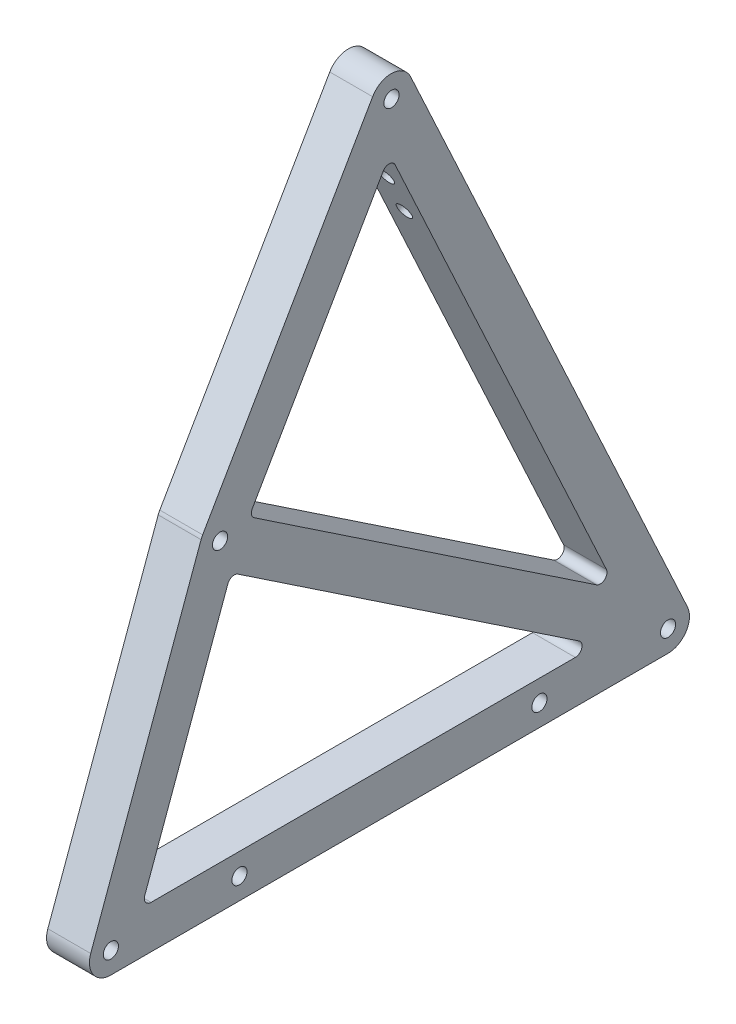
SolidWorks part; units mm, degrees
ref_plane "Front Plane" through (0, 0, 0) normal (0, 0, 1) x (1, 0, 0)
ref_plane "Top Plane" through (0, 0, 0) normal (0, 1, 0) x (1, 0, 0)
ref_plane "Right Plane" through (0, 0, 0) normal (1, 0, 0) x (0, 0, -1)
sketch "Sketch1" plane through (0, 0, 0) normal (1, 0, 0) x (0, 0, -1)
  line L0 (0, 0) -> (50.8, 87.9882) construction
  line L1 (0, 0) -> (-32.357, -88.9) construction
  line L2 (-32.357, -88.9) -> (132.743, -88.9) construction
  line L3 (132.743, -88.9) -> (0, 0) construction
  line L4 (0, 0) -> (117.1773, 0) construction
  line L5 (50.8, 87.9882) -> (132.743, -88.9) construction
  circle A0 centre (0, 0) radius 50.8 construction
  circle A1 centre (28.575, 49.4934) radius 6.35 construction
  circle A2 centre (47.4848, -31.8013) radius 6.35 construction
  dimension "D4" = 101.6
  dimension "D5" = 12.7
  dimension "D8" = 12.7
  dimension "D1" = 60
  dimension "D2" = 70
  dimension "D3" = 165.1
  dimension "D6" = 101.6
  dimension "D7" = 88.9
sketch "Sketch2" plane through (0, 0, 0) normal (1, 0, 0) x (0, 0, -1)
  line L0 (-23.2882, -82.55) -> (3.1967, -9.7834)
  line L1 (3.1967, -9.7834) -> (111.8498, -82.55)
  line L2 (111.8498, -82.55) -> (-23.2882, -82.55)
  line L3 (8.6152, 1.8728) -> (117.4643, -71.0251)
  line L4 (117.4643, -71.0251) -> (50.2711, 74.0229)
  line L5 (50.2711, 74.0229) -> (8.6152, 1.8728)
  line L6 (-41.4257, -95.25) -> (142.6829, -95.25)
  line L7 (142.6829, -95.25) -> (51.3289, 101.9534)
  line L8 (51.3289, 101.9534) -> (-5.4332, 3.6387)
  line L9 (-5.4332, 3.6387) -> (-41.4257, -95.25)
  line L10 (0, 0) -> (-32.357, -88.9) construction
  line L11 (0, 0) -> (50.8, 87.9882) construction
  line L12 (50.8, 87.9882) -> (132.743, -88.9) construction
  line L13 (132.743, -88.9) -> (0, 0) construction
  line L14 (-32.357, -88.9) -> (132.743, -88.9) construction
  line L15 (50.8, 87.9882) -> (132.743, -88.9) construction
  line L16 (132.743, -88.9) -> (0, 0) construction
  line L17 (-32.357, -88.9) -> (132.743, -88.9) construction
  line L18 (0, 0) -> (-32.357, -88.9) construction
  line L19 (0, 0) -> (50.8, 87.9882) construction
  circle A0 centre (0, 0) radius 2.25
  circle A1 centre (50.8, 87.9882) radius 2.25
  circle A2 centre (-32.357, -88.9) radius 2.25
  circle A3 centre (132.743, -88.9) radius 2.25
  circle A4 centre (5.743, -88.9) radius 2.25
  circle A5 centre (94.643, -88.9) radius 2.25
  dimension "D5" = 4.5
  dimension "D6" = 4.5
  dimension "D7" = 4.5
  dimension "D8" = 4.5
  dimension "D1" = 12.7
  dimension "D2" = 12.7
  dimension "D3" = 12.7
  dimension "D4" = 12.7
  dimension "D9" = 38.1
  dimension "D10" = 38.1
extrude "Boss-Extrude1" add sketch "Sketch2" along normal blind 12.7
fillet "Fillet1" radius 6.35 4 edges at (6.35, -95.25, 41.4257) (6.35, -95.25, -142.6829) (6.35, 101.9534, -51.3289) (6.35, 3.6387, 5.4332)
fillet "Fillet2" radius 2 6 edges at (6.35, 74.0229, -50.2711) (6.35, 1.8728, -8.6152) (6.35, -71.0251, -117.4643) (6.35, -82.55, -111.8498) (6.35, -82.55, 23.2882) (6.35, -9.7834, -3.1967)
sketch "Sketch3" plane through (0, 37.5902, -81.145) normal (0, 0.4203, -0.9074) x (-1, 0, 0)
  line L0 (0, -136.4618) -> (0, 58.6981) construction
  line L1 (0, 58.6981) -> (-12.7, 58.6981) construction
  circle A0 centre (-6.35, 33.2981) radius 2.25
  circle A1 centre (-6.35, 20.5981) radius 2.25
  point P8 (0, 0)
  dimension "D1" = 4.5
  dimension "D3" = 4.5
  dimension "D2" = 12.7
  dimension "D4" = 6.35
  dimension "D5" = 25.4
extrude "Cut-Extrude1" cut sketch "Sketch3" against normal up to next
